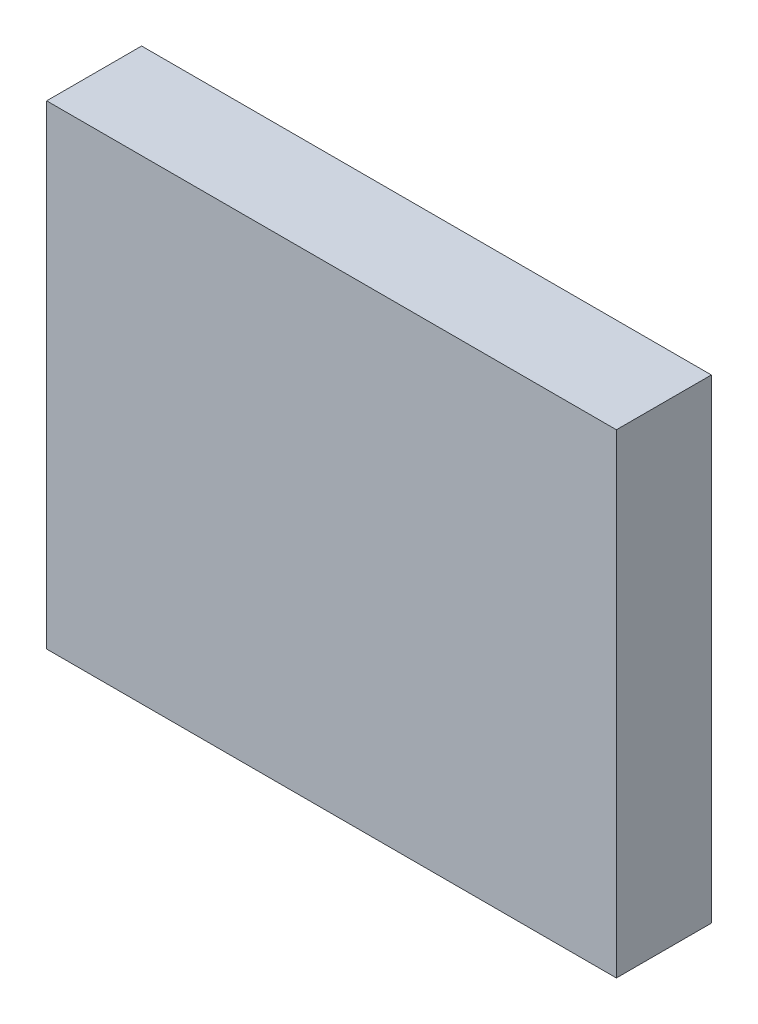
SolidWorks part; units mm, degrees
ref_plane "Plan de face" through (0, 0, 0) normal (0, 0, 1) x (1, 0, 0)
ref_plane "Plan de dessus" through (0, 0, 0) normal (0, 1, 0) x (1, 0, 0)
ref_plane "Plan de droite" through (0, 0, 0) normal (1, 0, 0) x (0, 0, -1)
sketch "Esquisse1" plane through (0, 0, 0) normal (0, 0, 1) x (1, 0, 0)
  line L1 (-30, -25) -> (30, -25)
  line L2 (-30, -25) -> (-30, 25)
  line L3 (-30, 25) -> (30, 25)
  line L4 (30, -25) -> (30, 25)
  line L5 (-30, -25) -> (30, 25) construction
  line L6 (-30, 25) -> (30, -25) construction
  point P0 (0, 0)
  dimension "D1" = 60
  dimension "D2" = 50
extrude "Boss.-Extru.1" add sketch "Esquisse1" along normal blind 10
